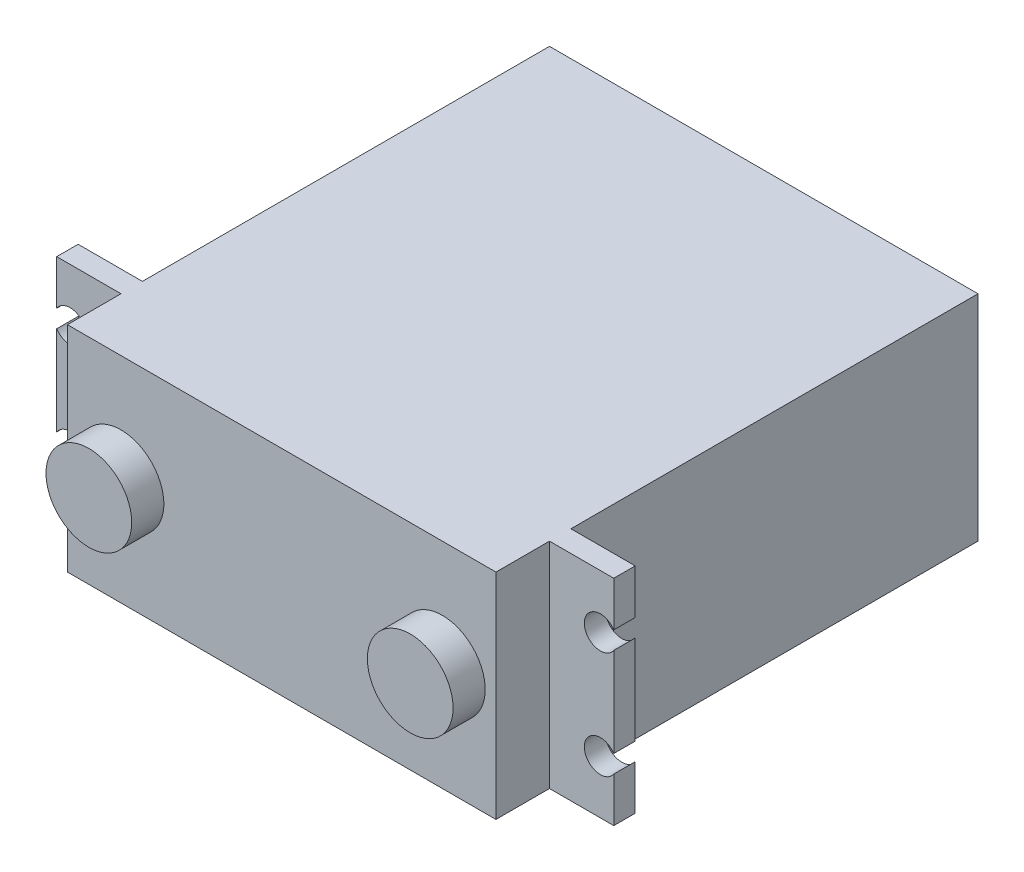
SolidWorks part; units mm, degrees
ref_plane "Plan de face" through (0, 0, 0) normal (0, 0, 1) x (1, 0, 0)
ref_plane "Plan de dessus" through (0, 0, 0) normal (0, 1, 0) x (1, 0, 0)
ref_plane "Plan de droite" through (0, 0, 0) normal (1, 0, 0) x (0, 0, -1)
sketch "Esquisse1" plane through (0, 0, 0) normal (0, 0, 1) x (1, 0, 0)
  line L1 (0, 0) -> (40, 0)
  line L2 (0, 0) -> (0, 20)
  line L3 (0, 20) -> (40, 20)
  line L4 (40, 0) -> (40, 20)
  dimension "D1" = 20
  dimension "D2" = 40
extrude "Boss.-Extru.1" add sketch "Esquisse1" along normal blind 45
sketch "Esquisse2" plane through (0, 0, 45) normal (0, 0, 1) x (1, 0, 0)
  line L0 (40, 20) -> (0, 20) construction
  line L1 (0, 20) -> (0, 0) construction
  line L2 (40, 0) -> (40, 20) construction
  circle A0 centre (5, 10) radius 4
  circle A1 centre (35, 10) radius 4
  dimension "D1" = 8
  dimension "D2" = 8
  dimension "D3" = 10
  dimension "D4" = 10
  dimension "D5" = 5
  dimension "D6" = 5
extrude "Boss.-Extru.2" add sketch "Esquisse2" along normal blind 3
sketch "Esquisse3" plane through (0, 0, 0) normal (-1, 0, 0) x (0, 0, 1)
  line L0 (45, 20) -> (0, 20) construction
  line L1 (38, 20) -> (40, 20)
  line L2 (38, 20) -> (38, 0)
  line L3 (38, 0) -> (40, 0)
  line L4 (40, 20) -> (40, 0)
  line L5 (45, 0) -> (0, 0) construction
  line L6 (45, 20) -> (45, 0) construction
  dimension "D1" = 2
  dimension "D2" = 5
extrude "Boss.-Extru.3" add sketch "Esquisse3" along normal blind 6
sketch "Esquisse4" plane through (40, 0, 0) normal (1, 0, 0) x (0, 0, -1)
  line L0 (-45, 20) -> (0, 20) construction
  line L1 (-40, 20) -> (-38, 20)
  line L2 (-40, 20) -> (-40, 0)
  line L3 (-40, 0) -> (-38, 0)
  line L4 (-38, 20) -> (-38, 0)
  line L5 (-45, 0) -> (0, 0) construction
  line L6 (-45, 0) -> (-45, 20) construction
  dimension "D1" = 5
  dimension "D2" = 2
extrude "Boss.-Extru.4" add sketch "Esquisse4" along normal blind 6
sketch "Esquisse5" plane through (0, 0, 40) normal (0, 0, 1) x (1, 0, 0)
  line L0 (40, 20) -> (40, 0) construction
  line L1 (40, 0) -> (40, 20) construction
  line L2 (0, 20) -> (0, 0) construction
  line L3 (-6, 0) -> (0, 0) construction
  line L4 (-6, 20) -> (0, 20) construction
  line L5 (46, 20) -> (40, 20) construction
  line L6 (46, 0) -> (40, 0) construction
  circle A0 centre (-4.75, 15) radius 1.5
  circle A1 centre (-4.75, 5) radius 1.5
  circle A2 centre (44.75, 15) radius 1.5
  circle A3 centre (44.75, 5) radius 1.5
  point P8 (0, 0)
  point P21 (43, 20)
  dimension "D1" = 3
  dimension "D2" = 3
  dimension "D3" = 3
  dimension "D4" = 3
  dimension "D5" = 4.75
  dimension "D6" = 4.75
  dimension "D7" = 4.75
  dimension "D8" = 4.75
  dimension "D9" = 5
  dimension "D10" = 5
  dimension "D11" = 5
  dimension "D12" = 5
extrude "Enlèv. mat.-Extru.1" cut sketch "Esquisse5" against normal blind 6
